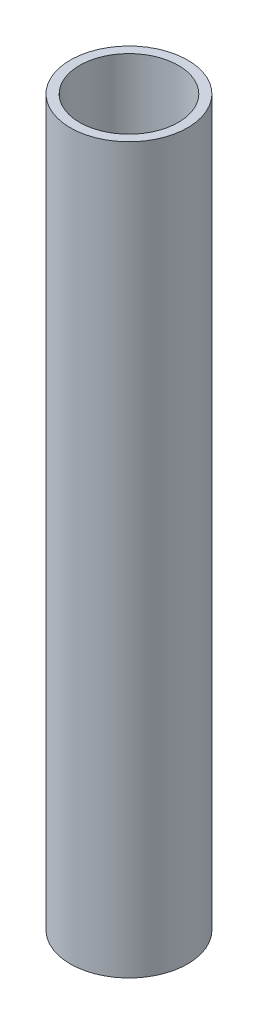
SolidWorks part; units mm, degrees
ref_plane "Front Plane" through (0, 0, 0) normal (0, 0, 1) x (1, 0, 0)
ref_plane "Top Plane" through (0, 0, 0) normal (0, 1, 0) x (1, 0, 0)
ref_plane "Right Plane" through (0, 0, 0) normal (1, 0, 0) x (0, 0, -1)
sketch "Sketch1" plane through (0, 0, 0) normal (0, 1, 0) x (1, 0, 0)
  circle A0 centre (0, 0) radius 25.4
  circle A1 centre (0, 0) radius 30.1625
  dimension "D1" = 50.8
  dimension "D2" = 60.325
extrude "Boss-Extrude1" add sketch "Sketch1" along normal mid plane 372.364
